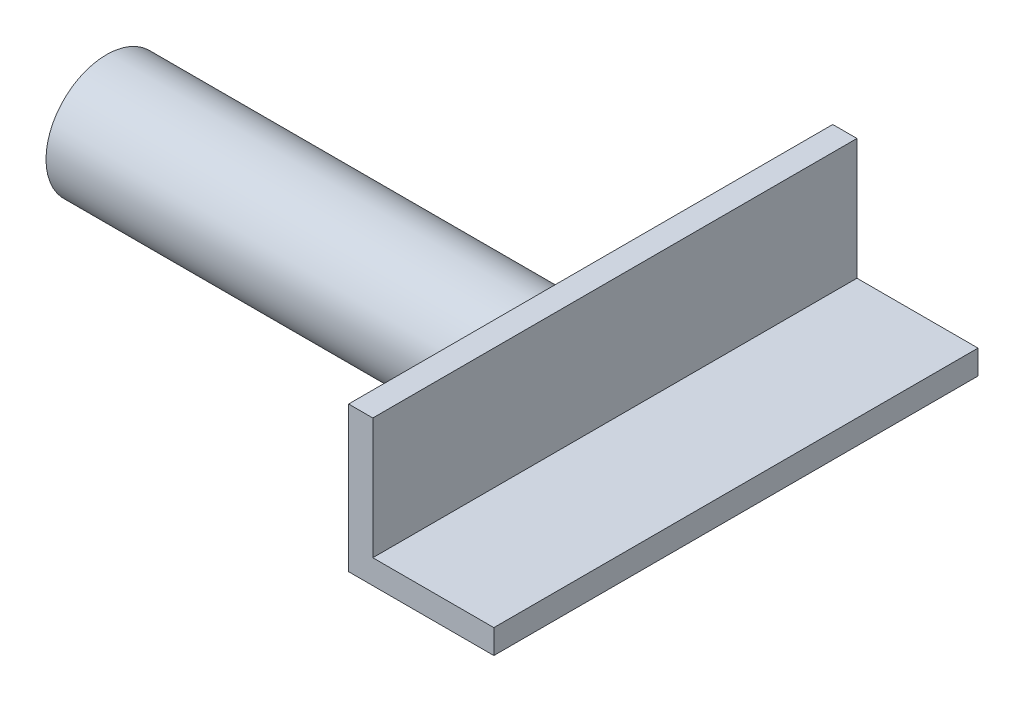
SolidWorks part; units mm, degrees
ref_plane "Plan de face" through (0, 0, 0) normal (0, 0, 1) x (1, 0, 0)
ref_plane "Plan de dessus" through (0, 0, 0) normal (0, 1, 0) x (1, 0, 0)
ref_plane "Plan de droite" through (0, 0, 0) normal (1, 0, 0) x (0, 0, -1)
sketch "Esquisse1" plane through (0, 0, 0) normal (0, 0, 1) x (1, 0, 0)
  line L0 (0, 0) -> (0, 12)
  line L1 (0, 12) -> (2, 12)
  line L2 (2, 12) -> (2, 2)
  line L3 (2, 2) -> (12, 2)
  line L4 (12, 2) -> (12, 0)
  line L5 (12, 0) -> (0, 0)
  dimension "D1" = 12
  dimension "D2" = 10
  dimension "D3" = 12
  dimension "D4" = 10
extrude "Boss.-Extru.1" add sketch "Esquisse1" along normal blind 40
sketch "Esquisse2" plane through (0, 0, 0) normal (-1, 0, 0) x (0, 0, 1)
  line L0 (40, 12) -> (0, 12) construction
  line L1 (0, 12) -> (0, 0) construction
  circle A0 centre (20, 2) radius 5
  dimension "D1" = 10
  dimension "D2" = 10
  dimension "D3" = 20
extrude "Boss.-Extru.2" add sketch "Esquisse2" along normal blind 40
